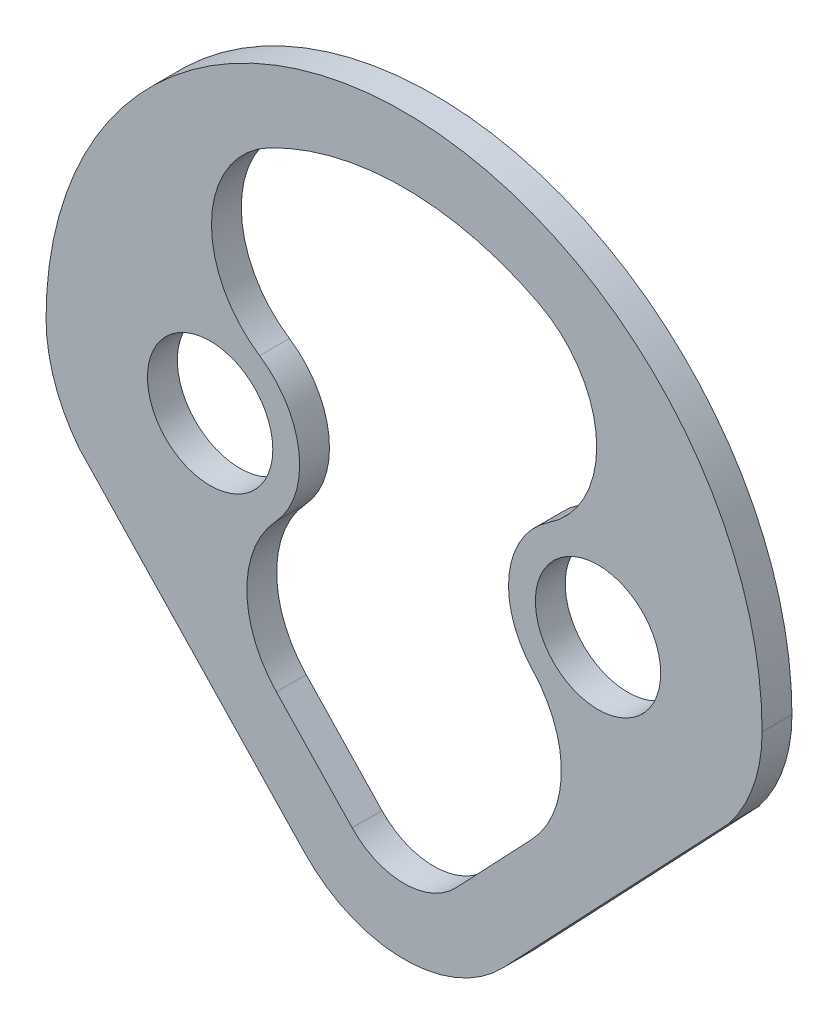
SolidWorks part; units mm, degrees
ref_plane "Front Plane" through (0, 0, 0) normal (0, 0, 1) x (1, 0, 0)
ref_plane "Top Plane" through (0, 0, 0) normal (0, 1, 0) x (1, 0, 0)
ref_plane "Right Plane" through (0, 0, 0) normal (1, 0, 0) x (0, 0, -1)
sketch "Sketch1" plane through (0, 0, 0) normal (0, 0, 1) x (1, 0, 0)
  line L0 (0, -50) -> (0, 50) construction
  line L1 (0, 0) -> (0, 40) construction
  line L2 (0, 40) -> (-32.5, 40) construction
  line L3 (-32.5, 40) -> (-60, 40) construction
  line L4 (-54.4228, 23.9093) -> (-16.6782, -15.8379)
  line L5 (-21.4045, 5.1135) -> (-8.7017, -8.2632)
  line L6 (21.4045, 5.1135) -> (8.7017, -8.2632)
  line L7 (54.4228, 23.9093) -> (16.6782, -15.8379)
  circle A0 centre (-32.5, 40) radius 10.5
  arc A1 (-21.5236, 29.7765) -> (-24.2185, 52.5067) centre (-32.5, 40) ccw
  arc A2 (60, 40) -> (-60, 40) centre (0, 40) ccw
  arc A3 (22.5728, 83.491) -> (-22.5728, 83.491) centre (0, 40) ccw
  arc A4 (-24.2185, 52.5067) -> (-22.15, 83.7035) centre (-14.2808, 67.5147) cw
  arc A5 (-21.4045, 5.1135) -> (-21.5236, 29.7765) centre (-8.352, 17.5084) cw
  arc A6 (-16.6782, -15.8379) -> (16.6782, -15.8379) centre (0, 0) ccw
  arc A7 (-60, 40) -> (-54.4228, 23.9093) centre (-34, 40) ccw
  circle A8 centre (0, 40) radius 49 construction
  arc A9 (-8.7017, -8.2632) -> (8.7017, -8.2632) centre (0, 0) ccw
  circle A10 centre (0, 40) radius 60 construction
  circle A11 centre (32.5, 40) radius 10.5
  arc A12 (21.4045, 5.1135) -> (21.5236, 29.7765) centre (8.352, 17.5084) ccw
  arc A13 (21.5236, 29.7765) -> (24.2185, 52.5067) centre (32.5, 40) cw
  arc A14 (24.2185, 52.5067) -> (22.15, 83.7035) centre (14.2808, 67.5147) ccw
  arc A15 (60, 40) -> (54.4228, 23.9093) centre (34, 40) cw
  point P4 (0, 0)
  point P12 (-25.0042, 6.5257)
  dimension "D1" = 21
  dimension "D2" = 15
  dimension "D3" = 120
  dimension "D5" = 18
  dimension "D8" = 11
  dimension "D9" = 26
  dimension "D10" = 18
  dimension "D6" = 32.5
  dimension "D7" = 40
  dimension "D4" = 11
extrude "Boss-Extrude1" add sketch "Sketch1" along normal blind 5 contours A15 A2 A7 L4 A6 L7 A14 A13 A12 L6 A9 L5 A5 A1 A4 A3 A0 A11
